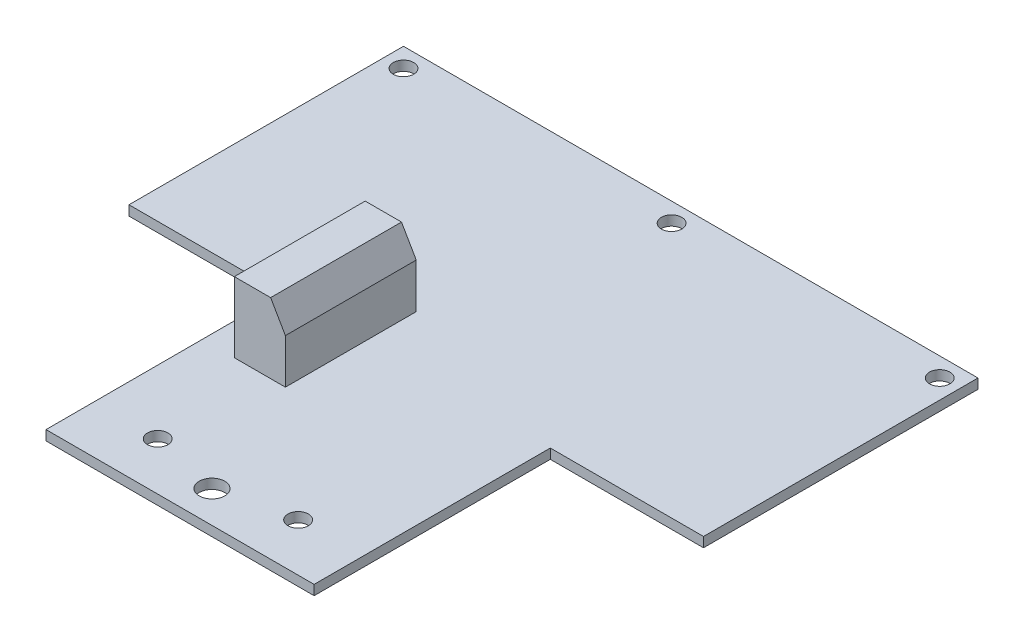
SolidWorks part; units mm, degrees
material "Плата обработки данных, простая"
ref_plane "Front" through (0, 0, 0) normal (0, 0, 1) x (1, 0, 0)
ref_plane "Top" through (0, 0, 0) normal (0, 1, 0) x (1, 0, 0)
ref_plane "Right" through (0, 0, 0) normal (1, 0, 0) x (0, 0, -1)
sketch "Эскиз1" plane through (0, 0, 0) normal (0, 1, 0) x (1, 0, 0)
  line L0 (0, 0) -> (0, 115.7862) construction
  line L1 (-21, 0) -> (21, 0)
  line L2 (21, 0) -> (21, 37)
  line L3 (21, 37) -> (45, 37)
  line L4 (45, 37) -> (45, 80)
  line L5 (45, 80) -> (-45, 80)
  line L6 (0, 77) -> (42, 77) construction
  line L7 (-21, 0) -> (-21, 37)
  line L8 (-21, 37) -> (-45, 37)
  line L9 (-45, 37) -> (-45, 80)
  circle A0 centre (11, 7.5) radius 1.6
  circle A1 centre (42, 77) radius 1.6
  circle A2 centre (0, 77) radius 1.6
  circle A3 centre (0, 5) radius 2
  circle A4 centre (-42, 77) radius 1.6
  circle A5 centre (-11, 7.5) radius 1.6
  point P24 (0, 80)
  dimension "D5" = 3.2
  dimension "D6" = 3.2
  dimension "D7" = 3.2
  dimension "D12" = 4
  dimension "D1" = 90
  dimension "D2" = 43
  dimension "D3" = 42
  dimension "D4" = 37
  dimension "D8" = 11
  dimension "D9" = 7.5
  dimension "D10" = 77
  dimension "D11" = 42
  dimension "D13" = 5
extrude "Бобышка-Вытянуть1" add sketch "Эскиз1" along normal blind 1.54
sketch "Эскиз2" plane through (0, 1.54, 0) normal (0, 1, 0) x (1, 0, 0)
  line L0 (-45, 37) -> (-21, 37) construction
  line L1 (-16, 24.5) -> (-8, 24.5)
  line L2 (-16, 24.5) -> (-16, 45)
  line L3 (-16, 45) -> (-8, 45)
  line L4 (-8, 24.5) -> (-8, 45)
  line L5 (-21, 37) -> (-21, 0) construction
  dimension "D1" = 20.5
  dimension "D2" = 8
  dimension "D3" = 8
  dimension "D4" = 5
extrude "Бобышка-Вытянуть2" add sketch "Эскиз2" along normal blind 11
chamfer "Фаска1" distance 4 angle 30 1 edges at (-8, 12.54, -34.75)
